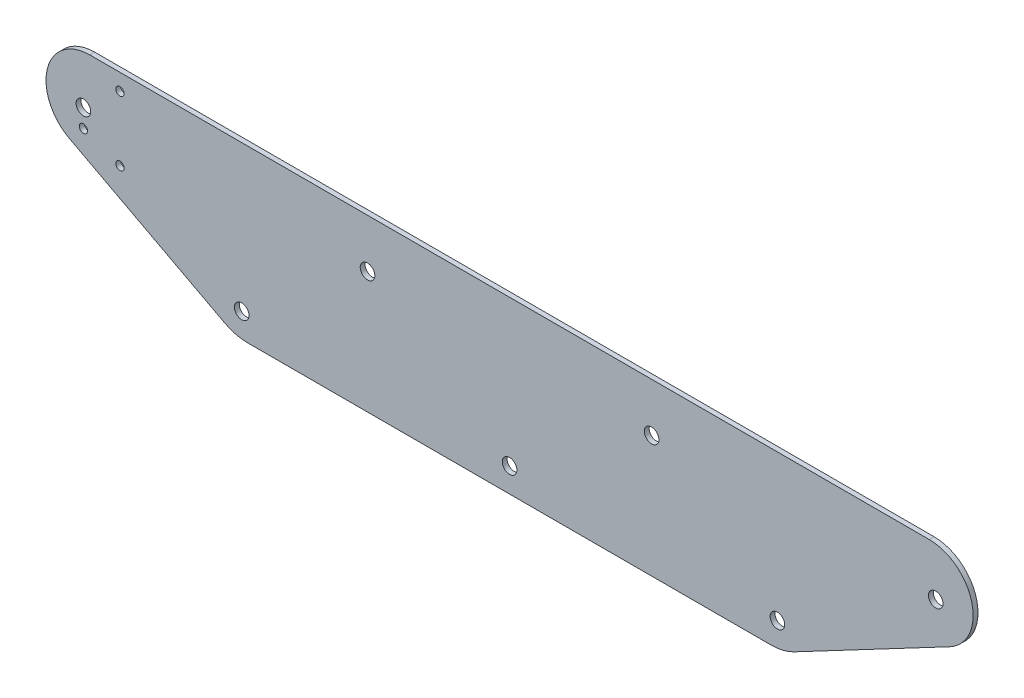
SolidWorks part; units mm, degrees
ref_plane "Plan de face" through (0, 0, 0) normal (0, 0, 1) x (1, 0, 0)
ref_plane "Plan de dessus" through (0, 0, 0) normal (0, 1, 0) x (1, 0, 0)
ref_plane "Plan de droite" through (0, 0, 0) normal (1, 0, 0) x (0, 0, -1)
sketch "Esquisse1" plane through (0, 0, 0) normal (0, 0, 1) x (1, 0, 0)
  line L0 (0, 0) -> (0, 122.747) construction
  line L1 (-175, -20) -> (175, -20) construction
  line L2 (-175, -20) -> (-175, 20) construction
  line L3 (-175, 20) -> (175, 20) construction
  line L4 (175, -20) -> (175, 20) construction
  line L5 (-175, -20) -> (175, 20) construction
  line L6 (-175, 20) -> (175, -20) construction
  line L7 (-1220, 0) -> (-110, 0) construction
  line L8 (-244.959, 40) -> (-110, 40)
  line L9 (110, 40) -> (244.959, 40)
  line L10 (110, 0) -> (110, -20) construction
  line L11 (110, -20) -> (-110, -20) construction
  line L12 (-110, 0) -> (-110, -20) construction
  line L13 (110, 0) -> (-110, -20) construction
  line L14 (110, -20) -> (-110, 0) construction
  line L15 (-244.959, 40) -> (-112.4795, -30)
  line L16 (-112.4795, -30) -> (112.4795, -30)
  line L17 (244.959, 40) -> (112.4795, -30)
  line L18 (-175, 20) -> (-58.3333, 20) construction
  line L19 (-58.3333, 20) -> (58.3333, 20) construction
  line L20 (58.3333, 20) -> (175, 20) construction
  line L21 (110, 0) -> (193.5165, 0) construction
  line L22 (110, 95) -> (-110, 95) construction
  line L23 (110, 95) -> (110, 40) construction
  line L24 (-110, 40) -> (110, 40)
  line L25 (-110, 95) -> (-110, 40) construction
  line L26 (110, 95) -> (-110, 0) construction
  line L27 (110, 0) -> (-110, 95) construction
  circle A0 centre (-175, 20) radius 3
  circle A1 centre (-110, -20) radius 3
  circle A2 centre (110, -20) radius 3
  circle A3 centre (175, 20) radius 3
  circle A4 centre (0, -20) radius 3
  circle A5 centre (-58.3333, 20) radius 3
  circle A6 centre (58.3333, 20) radius 3
  circle A7 centre (0, 78.03) radius 3 construction
  point P0 (0, 0)
  point P8 (0, -10)
  point P20 (0, 47.5)
  point P21 (0, -30)
  point P31 (0, 47.5)
  dimension "D8" = 6
  dimension "D10" = 58.03
  dimension "D1" = 350
  dimension "D2" = 40
  dimension "D3" = 220
  dimension "D4" = 20
  dimension "D5" = 15
  dimension "D6" = 10
  dimension "D7" = 10
  dimension "D9" = 55
extrude "Boss.-Extru.1" add sketch "Esquisse1" along normal blind 2
fillet "Congé1" radius 18 2 edges at (-244.959, 40, 1) (244.959, 40, 1)
fillet "Congé2" radius 20 2 edges at (-112.4795, -30, 1) (112.4795, -30, 1)
hole_wizard "Dégagement M31" positions "Esquisse3" profile "Esquisse2" hole size "M3" standard "Ansi Metric" end condition through all
sketch "Esquisse3" plane through (0, 0, 0) normal (0, 0, -1) x (-1, 0, 0)
  line L0 (175, 12.5) -> (175, 20)
  line L1 (160, 6.7712) -> (160, 33.2288)
  circle A0 centre (175, 20) radius 7.5
  circle A1 centre (175, 20) radius 20
  point P0 (160, 33.2288)
  point P4 (175, 12.5)
  point P29 (160, 6.7712)
  dimension "D2" = 15
  dimension "D3" = 40
  dimension "D1" = 15
sketch "Esquisse2" plane through (-160, 33.2288, 0) normal (1, 0, 0) x (0, 1, 0)
  line L0 (0, 0) -> (0, 2)
  line L1 (0, 2) -> (1.7, 2)
  line L2 (1.7, 2) -> (1.7, 0)
  line L5 (1.7, 0) -> (0, 0)
  line L11 (0, -6.35) -> (0, 107.95) construction
  dimension "Diamètre du perçage jusqu'au prochain" = 3.4
  dimension "Profondeur du perçage jusqu'au prochain" = 2
